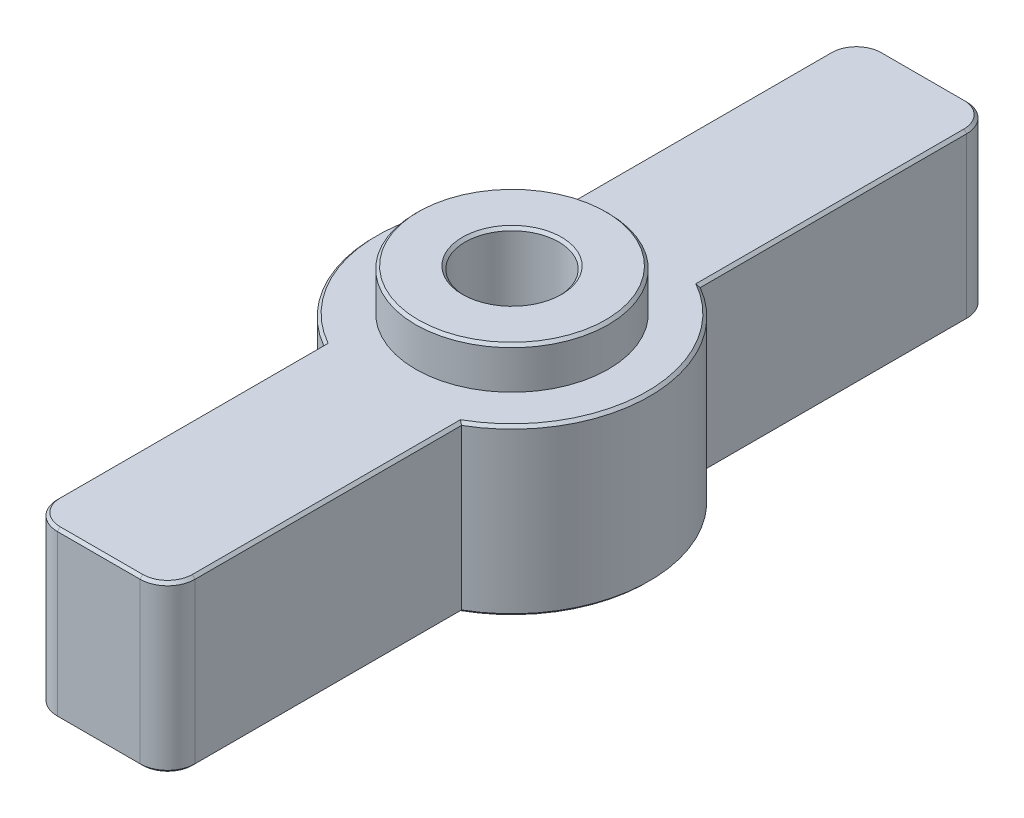
SolidWorks part; units mm, degrees
ref_plane "Front Plane" through (0, 0, 0) normal (0, 0, 1) x (1, 0, 0)
ref_plane "Top Plane" through (0, 0, 0) normal (0, 1, 0) x (1, 0, 0)
ref_plane "Right Plane" through (0, 0, 0) normal (1, 0, 0) x (0, 0, -1)
other "Configuration Table"
sketch "草图1" plane through (0, 0, 0) normal (0, 1, 0) x (1, 0, 0)
  line L0 (-5, 0) -> (5, 0) construction
  line L1 (-5, -28) -> (-5, -8.6603)
  line L2 (5, -28) -> (5, -8.6603)
  line L3 (-3, 30) -> (3, 30)
  line L4 (-3, -30) -> (3, -30)
  line L5 (-5, 8.6603) -> (-5, 28)
  line L6 (5, 8.6603) -> (5, 28)
  arc A0 (-5, 8.6603) -> (-5, -8.6603) centre (0, 0) ccw
  arc A1 (3, -30) -> (5, -28) centre (3, -28) ccw
  arc A2 (-3, -30) -> (-5, -28) centre (-3, -28) cw
  arc A3 (5, 28) -> (3, 30) centre (3, 28) ccw
  arc A4 (-5, 28) -> (-3, 30) centre (-3, 28) cw
  arc A5 (5, -8.6603) -> (5, 8.6603) centre (0, 0) ccw
  point P6 (0, 0)
  point P9 (-5, 0)
  point P12 (5, 0)
  dimension "D1" = 60
  dimension "D2" = 2
  dimension "D3" = 10
extrude "凸台-拉伸1" add sketch "草图1" along normal blind 12
sketch "草图2" plane through (0, 0, 0) normal (0, -1, 0) x (1, 0, 0)
  circle A0 centre (0, 0) radius 6.75
extrude "切除-拉伸1" cut sketch "草图2" against normal blind 8.5
sketch "草图4" plane through (0, 12, 0) normal (0, 1, 0) x (1, 0, 0)
  circle A0 centre (0, 0) radius 7
  dimension "D1" = 14
extrude "凸台-拉伸2" add sketch "草图4" along normal blind 3
sketch "草图3" plane through (0, 8.5, 0) normal (0, -1, 0) x (1, 0, 0)
  circle A0 centre (0, 0) radius 3.4
  dimension "D1" = 6.8
extrude "切除-拉伸2" cut sketch "草图3" against normal through all
chamfer "倒角1" distance 0.2 angle 45 27 edges at (5, 12, 18.3301) (4.4142, 12, 29.4142) (0, 12, 30) (-4.4142, 12, 29.4142) (-5, 12, 18.3301) (-10, 12, 0) (0, 15, 7) (0, 15, -3.4) (5, 0, -18.3301) (4.4142, 0, -29.4142) (0, 0, -30) (-4.4142, 0, -29.4142) (-5, 0, -18.3301) (-5, 0, 18.3301) (-4.4142, 0, 29.4142) (0, 0, 30) (4.4142, 0, 29.4142) (5, 0, 18.3301) (-10, 0, 0) (0, 0, -6.75) (-5, 12, -18.3301) (-4.4142, 12, -29.4142) (0, 12, -30) (4.4142, 12, -29.4142) (5, 12, -18.3301) (10, 12, 0) (10, 0, 0)
